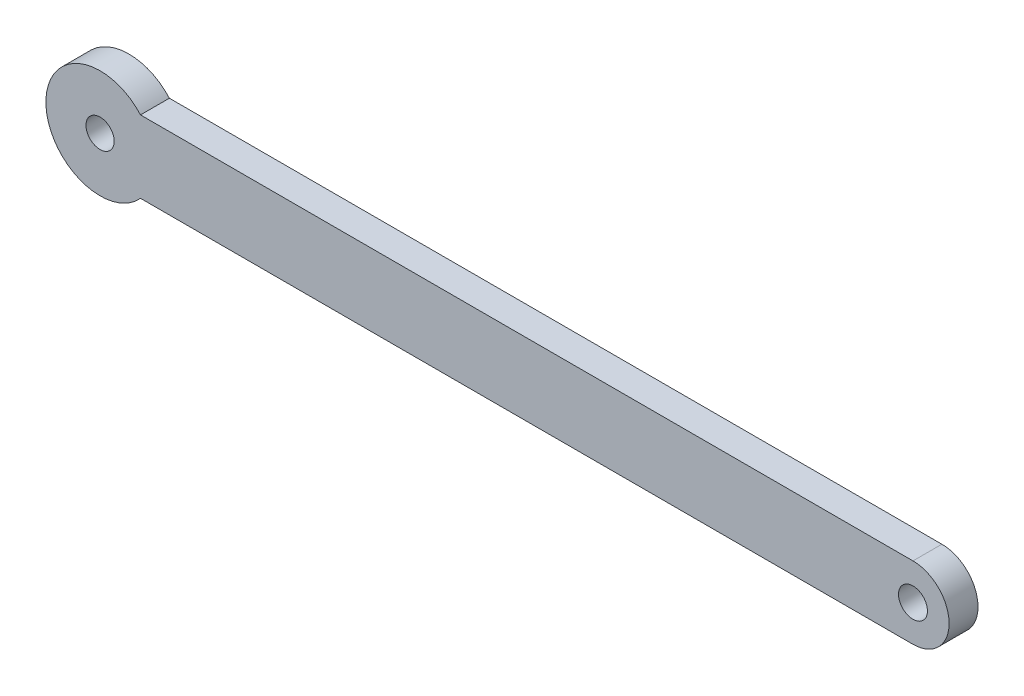
SolidWorks part; units mm, degrees
ref_plane "前视基准面" through (0, 0, 0) normal (0, 0, 1) x (1, 0, 0)
ref_plane "上视基准面" through (0, 0, 0) normal (0, 1, 0) x (1, 0, 0)
ref_plane "右视基准面" through (0, 0, 0) normal (1, 0, 0) x (0, 0, -1)
sketch "草图1" plane through (0, 0, 0) normal (0, 0, 1) x (1, 0, 0)
  line L0 (0, 0) -> (112.5, 0) construction
  line L1 (1.65, 0) -> (-1.65, 0) construction
  line L2 (5.5902, 5) -> (112.5, 5)
  line L3 (5.5902, -5) -> (112.5, -5)
  arc A1 (112.5, -5) -> (112.5, 5) centre (112.5, 0) ccw
  circle A2 centre (112.5, 0) radius 2
  circle A3 centre (0, 0) radius 1.95
  arc A4 (5.5902, 5) -> (5.5902, -5) centre (0, 0) ccw
  point P5 (56.25, 0)
extrude "凸台-拉伸1" add sketch "草图1" along normal mid plane 4
